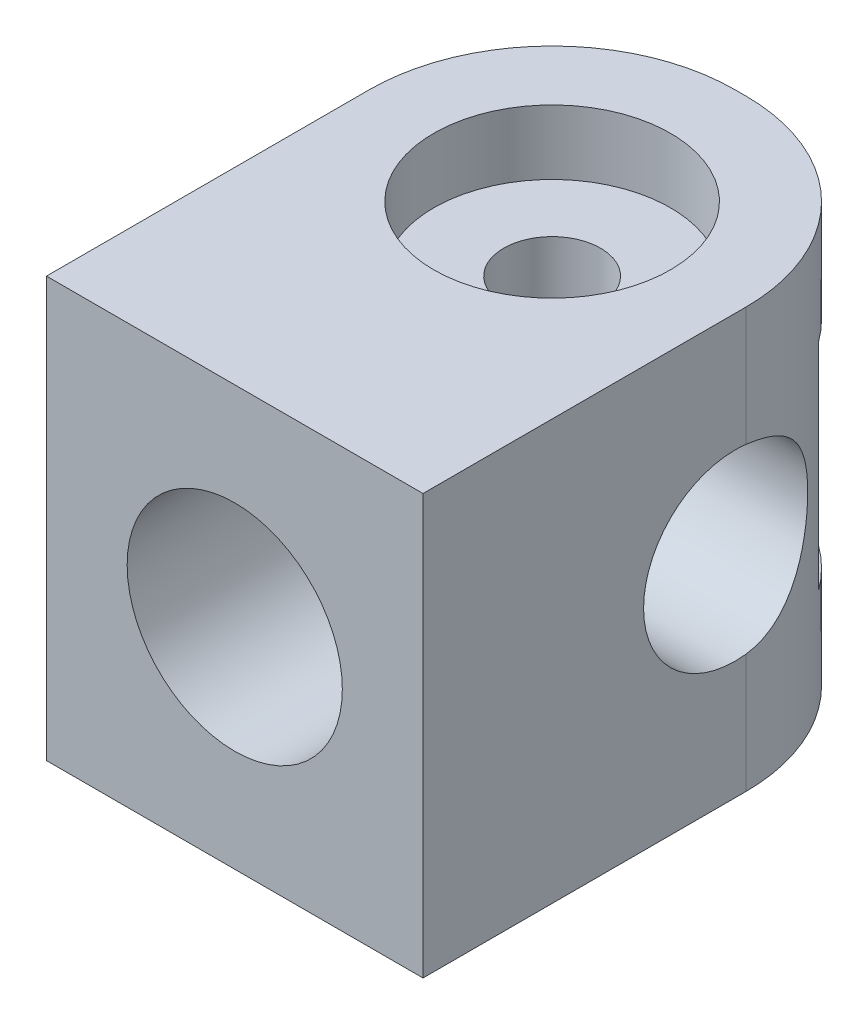
SolidWorks part; units mm, degrees
ref_plane "Plan de face" through (0, 0, 0) normal (0, 0, 1) x (1, 0, 0)
ref_plane "Plan de dessus" through (0, 0, 0) normal (0, 1, 0) x (1, 0, 0)
ref_plane "Plan de droite" through (0, 0, 0) normal (1, 0, 0) x (0, 0, -1)
sketch "Esquisse1" plane through (0, 0, 0) normal (0, 0, 1) x (1, 0, 0)
  line L1 (0, 0) -> (35, 0)
  line L2 (0, 0) -> (0, -39)
  line L3 (0, -39) -> (35, -39)
  line L4 (35, 0) -> (35, -39)
  dimension "D1" = 35
  dimension "D2" = 39
extrude "Boss.-Extru.1" add sketch "Esquisse1" along normal blind 47
sketch "Esquisse2" plane through (0, 0, 47) normal (0, 0, 1) x (1, 0, 0)
  line L0 (0, 0) -> (35, -39)
  circle A0 centre (17.5, -19.5) radius 10
extrude "Enlèv. mat.-Extru.1" cut sketch "Esquisse2" against normal blind 20 contours L0 A0 | L0 A0
fillet "Congé1" radius 17 2 edges at (0, -19.5, 0) (35, -19.5, 0)
sketch "Esquisse3" plane through (0, 0, 0) normal (0, 0, -1) x (-1, 0, 0)
  line L0 (-35, -39) -> (-35, -29.5)
  line L1 (0, 0) -> (0, -39) construction
  line L2 (-35, -29.5) -> (0, -29.5)
  line L3 (-35, -29.5) -> (-35, -9.5)
  line L4 (-35, -9.5) -> (0, -9.5)
  line L5 (0, -29.5) -> (0, -9.5)
  line M5 (-17, -39) -> (-17, 0)
  line M7 (-18, 0) -> (-18, -39)
  dimension "D1" = 9.5
  dimension "D2" = 20
extrude "Enlèv. mat.-Extru.2" cut sketch "Esquisse3" against normal blind 7 contours L4 L2 M7 M5 | L4 L3 L2 M7 | L2 L5 L4 M5
sketch "Esquisse4" plane through (35, 0, 0) normal (1, 0, 0) x (0, 0, -1)
  line L0 (-47, -39) -> (-18, -39)
  line L1 (-47, -39) -> (-17, -39) construction
  line L2 (-18, -39) -> (-18, 0)
  line L3 (-47, 0) -> (-17, 0) construction
  circle A0 centre (-18, -19.5) radius 8.5
  line M3 (-17, -39) -> (-17, 0)
  dimension "D2" = 17
  dimension "D1" = 29
extrude "Enlèv. mat.-Extru.3" cut sketch "Esquisse4" against normal blind 29 contours L2 A0 | A0 M3 | L2 A0 M3
sketch "Esquisse5" plane through (0, 0, 0) normal (0, 1, 0) x (1, 0, 0)
  line L0 (17.5, -47) -> (17.5, -17.5)
  line L1 (35, -47) -> (0, -47) construction
  circle A0 centre (17.5, -17.5) radius 4.5
  circle A1 centre (17.5, -17.5) radius 11
  dimension "D1" = 9
  dimension "D2" = 29.5
extrude "Enlèv. mat.-Extru.4" cut sketch "Esquisse5" against normal through all
sketch "Esquisse7" plane through (0, 0, 0) normal (0, 1, 0) x (1, 0, 0)
  circle A0 centre (17.5, -17.5) radius 11
extrude "Enlèv. mat.-Extru.5" cut sketch "Esquisse7" against normal blind 6
sketch "Esquisse8" plane through (0, -39, 0) normal (0, -1, 0) x (1, 0, 0)
  circle A0 centre (17.5, 17.5) radius 11
extrude "Enlèv. mat.-Extru.6" cut sketch "Esquisse8" against normal blind 6
sketch "Esquisse10" plane through (0, 0, 0) normal (-1, 0, 0) x (0, 0, 1)
  circle A0 centre (18, -19.5) radius 4.5
  circle A1 centre (18, -19.5) radius 8.5
  circle A2 centre (18, -19.5) radius 8.5
  line M3 (17, 0) -> (17, -39)
  dimension "D2" = 9
  dimension "D1" = 0
extrude "Enlèv. mat.-Extru.7" cut sketch "Esquisse10" against normal blind 6 contours A0 M3 | A0 M3
